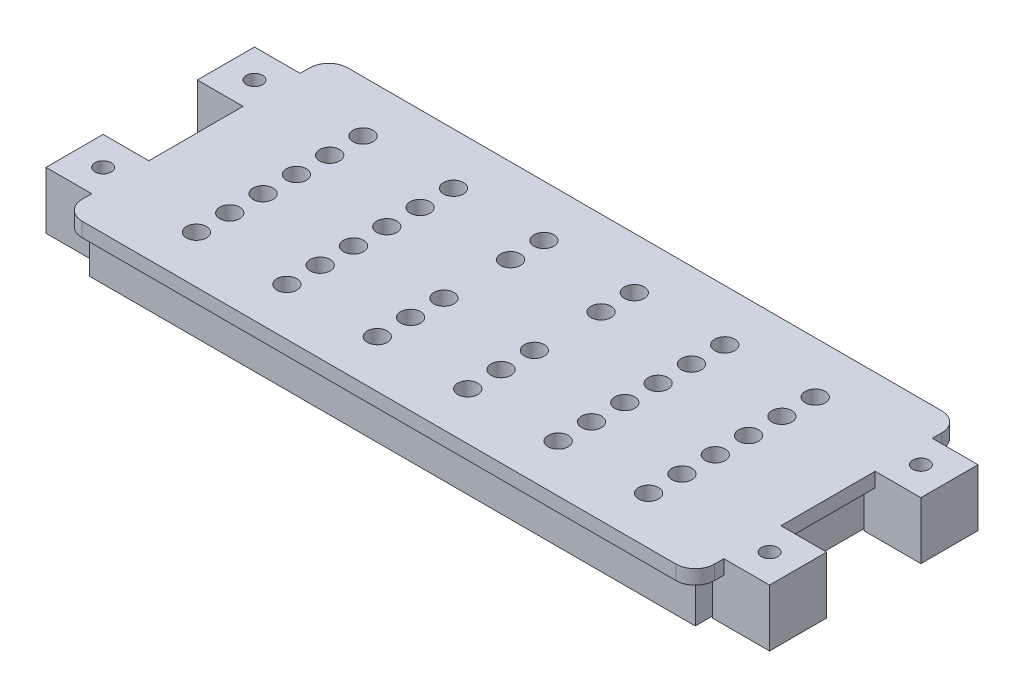
SolidWorks part; units mm, degrees
ref_plane "Front Plane" through (0, 0, 0) normal (0, 0, 1) x (1, 0, 0)
ref_plane "Top Plane" through (0, 0, 0) normal (0, 1, 0) x (1, 0, 0)
ref_plane "Right Plane" through (0, 0, 0) normal (1, 0, 0) x (0, 0, -1)
ref_plane "Plane_PlateBottom" through (0, 52, 0) normal (0, 1, 0) x (1, 0, 0)
sketch "Sk_Plate" plane through (0, 52, 0) normal (0, 1, 0) x (1, 0, 0)
  line L0 (4, 0) -> (128.8, 0)
  line L1 (132.8, 4) -> (132.8, 51.8)
  line L2 (128.8, 55.8) -> (4, 55.8)
  line L3 (0, 51.8) -> (0, 4)
  arc A0 (128.8, 0) -> (132.8, 4) centre (128.8, 4) ccw
  arc A1 (132.8, 51.8) -> (128.8, 55.8) centre (128.8, 51.8) ccw
  arc A2 (4, 55.8) -> (0, 51.8) centre (4, 51.8) ccw
  arc A3 (0, 4) -> (4, 0) centre (4, 4) ccw
extrude "Top Plate" add sketch "Sk_Plate" along normal blind 3
ref_plane "Plane_LidBottom" through (0, 43, 0) normal (0, 1, 0) x (1, 0, 0)
sketch "Sk_TabBlocks" plane through (0, 43, 0) normal (0, 1, 0) x (1, 0, 0)
  line L1 (-9.6, 6) -> (2.4, 6)
  line L2 (-9.6, 6) -> (-9.6, 18)
  line L3 (-9.6, 18) -> (2.4, 18)
  line L4 (2.4, 6) -> (2.4, 18)
  line L6 (130.4, 6) -> (142.4, 6)
  line L7 (130.4, 6) -> (130.4, 18)
  line L8 (130.4, 18) -> (142.4, 18)
  line L9 (142.4, 6) -> (142.4, 18)
  line L11 (-9.6, 37.8) -> (2.4, 37.8)
  line L12 (-9.6, 37.8) -> (-9.6, 49.8)
  line L13 (-9.6, 49.8) -> (2.4, 49.8)
  line L14 (2.4, 37.8) -> (2.4, 49.8)
  line L16 (130.4, 37.8) -> (142.4, 37.8)
  line L17 (130.4, 37.8) -> (130.4, 49.8)
  line L18 (130.4, 49.8) -> (142.4, 49.8)
  line L19 (142.4, 37.8) -> (142.4, 49.8)
extrude "Tab Blocks" add sketch "Sk_TabBlocks" along normal blind 12
sketch "Sk_Skirt" plane through (0, 43, 0) normal (0, 1, 0) x (1, 0, 0)
  line L1 (2.75, 2.75) -> (130.05, 2.75)
  line L2 (2.75, 2.75) -> (2.75, 53.05)
  line L3 (2.75, 53.05) -> (130.05, 53.05)
  line L4 (130.05, 2.75) -> (130.05, 53.05)
  line L6 (5.15, 5.15) -> (128.35, 5.15)
  line L7 (5.15, 5.15) -> (5.15, 51.35)
  line L8 (5.15, 51.35) -> (128.35, 51.35)
  line L9 (128.35, 5.15) -> (128.35, 51.35)
extrude "Locating Skirt" add sketch "Sk_Skirt" along normal blind 9
sketch "Sk_TabHoles" plane through (0, 0, 0) normal (0, 1, 0) x (1, 0, 0)
  circle A0 centre (-3.6, 12) radius 1.7
  circle A1 centre (-3.6, 43.8) radius 1.7
  circle A2 centre (136.4, 12) radius 1.7
  circle A3 centre (136.4, 43.8) radius 1.7
extrude "M3 Clearance Holes" cut sketch "Sk_TabHoles" against normal through all and the other way through all
sketch "Sk_Vents" plane through (0, 52, 0) normal (0, 1, 0) x (1, 0, 0)
  circle A0 centre (18, 10) radius 2.1
  circle A1 centre (18, 17) radius 2.1
  circle A2 centre (18, 24) radius 2.1
  circle A3 centre (18, 31) radius 2.1
  circle A4 centre (18, 38) radius 2.1
  circle A5 centre (18, 45) radius 2.1
  circle A6 centre (37, 10) radius 2.1
  circle A7 centre (37, 17) radius 2.1
  circle A8 centre (37, 24) radius 2.1
  circle A9 centre (37, 31) radius 2.1
  circle A10 centre (37, 38) radius 2.1
  circle A11 centre (37, 45) radius 2.1
  circle A12 centre (56, 10) radius 2.1
  circle A13 centre (56, 17) radius 2.1
  circle A14 centre (56, 24) radius 2.1
  circle A15 centre (56, 38) radius 2.1
  circle A16 centre (56, 45) radius 2.1
  circle A17 centre (75, 10) radius 2.1
  circle A18 centre (75, 17) radius 2.1
  circle A19 centre (75, 24) radius 2.1
  circle A20 centre (75, 38) radius 2.1
  circle A21 centre (75, 45) radius 2.1
  circle A22 centre (94, 10) radius 2.1
  circle A23 centre (94, 17) radius 2.1
  circle A24 centre (94, 24) radius 2.1
  circle A25 centre (94, 31) radius 2.1
  circle A26 centre (94, 38) radius 2.1
  circle A27 centre (94, 45) radius 2.1
  circle A28 centre (113, 10) radius 2.1
  circle A29 centre (113, 17) radius 2.1
  circle A30 centre (113, 24) radius 2.1
  circle A31 centre (113, 31) radius 2.1
  circle A32 centre (113, 38) radius 2.1
  circle A33 centre (113, 45) radius 2.1
extrude "Vent Holes" cut sketch "Sk_Vents" along normal blind 3
